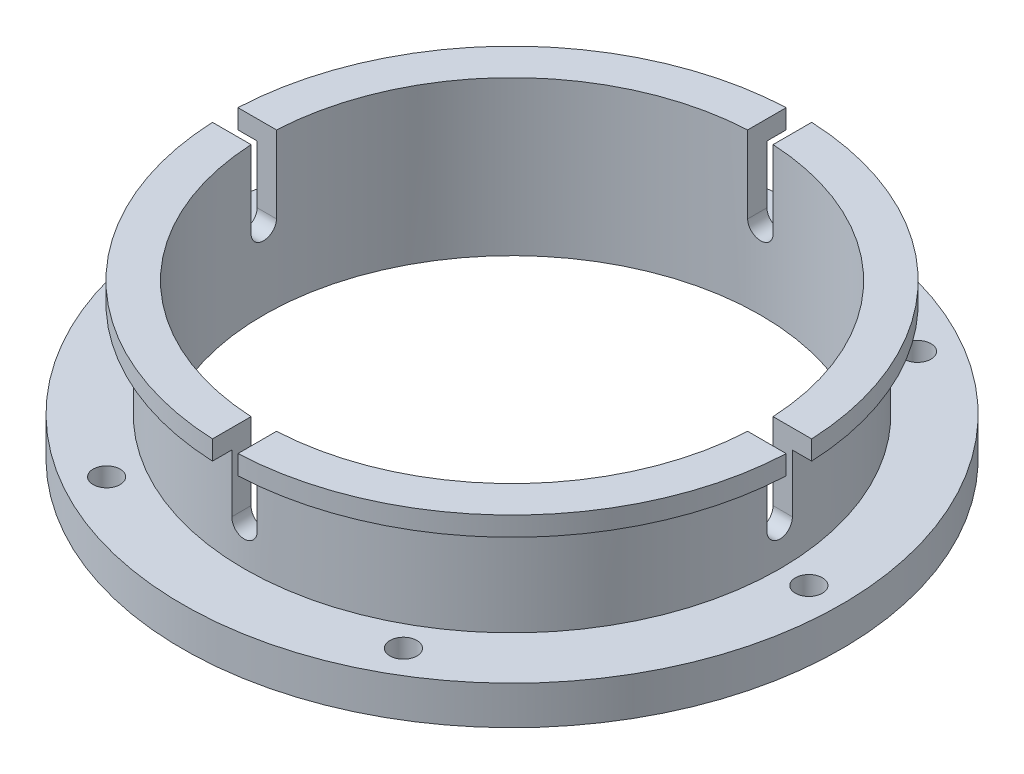
SolidWorks part; units mm, degrees
ref_plane "Front Plane" through (0, 0, 0) normal (0, 0, 1) x (1, 0, 0)
ref_plane "Top Plane" through (0, 0, 0) normal (0, 1, 0) x (1, 0, 0)
ref_plane "Right Plane" through (0, 0, 0) normal (1, 0, 0) x (0, 0, -1)
sketch "Sketch1" plane through (0, 0, 0) normal (0, 1, 0) x (1, 0, 0)
  circle A0 centre (0, 0) radius 32.45
  dimension "D1" = 64.9
sketch "Sketch2" plane through (0, 0, 0) normal (0, 0, 1) x (1, 0, 0)
  line L0 (-32.25, 20) -> (-32.25, 0)
  line L1 (32.45, 0) -> (-32.45, 0) construction
  line L2 (-32.25, 20) -> (-37.25, 20)
  line L3 (-37.25, 20) -> (-37.25, 17.5)
  line L4 (-37.25, 17.5) -> (-34.75, 17.5)
  line L5 (-34.75, 17.5) -> (-34.75, 5)
  line L6 (-34.75, 5) -> (-42.75, 5)
  line L7 (-42.75, 5) -> (-42.75, 0)
  line L8 (-42.75, 0) -> (-32.25, 0)
  line L9 (0, 0) -> (0, 50000) construction
  dimension "D1" = 10.5
  dimension "D2" = 2.5
  dimension "D3" = 5
  dimension "D4" = 2.5
  dimension "D5" = 20
  dimension "D6" = 5
  dimension "D7" = 2.5
  dimension "D8" = 32.25
revolve "Revolve1" add sketch "Sketch2" angle 360 about L9
sketch "Sketch3" plane through (0, 0, 0) normal (1, 0, 0) x (0, 0, -1)
  line L0 (37.25, 20) -> (-37.25, 20) construction
  line L1 (-1.65, 30) -> (1.65, 30)
  line L2 (-1.65, 30) -> (-1.65, 10)
  line L4 (1.65, 30) -> (1.65, 10)
  line L5 (-1.65, 30) -> (1.65, 10) construction
  line L6 (-1.65, 10) -> (1.65, 30) construction
  arc A0 (-1.65, 10) -> (1.65, 10) centre (0, 10) ccw
  point P0 (0, 20)
  dimension "D2" = 1.65
  dimension "D1" = 3.3
  dimension "D3" = 10
extrude "Cut-Extrude1" cut sketch "Sketch3" against normal through all both and the other way through all
pattern_circular "CirPattern1" count 4 over 360 about axis through (0, 0, 0) along (0, -1, 0) of "Cut-Extrude1"
sketch "Sketch4" plane through (0, 5, 0) normal (0, 1, 0) x (1, 0, 0)
  circle A0 centre (-38.5, 0) radius 1.75
  circle A1 centre (-38.5, 0) radius 3.5 construction
  dimension "D1" = 3.5
  dimension "D3" = 7
  dimension "D2" = 38.5
extrude "Cut-Extrude2" cut sketch "Sketch4" against normal blind 10
pattern_circular "CirPattern2" count 6 over 360 about axis through (0, 0, 0) along (0, 1, 0) of "Cut-Extrude2"
equation "\"D8@Sketch2\"=64.5/2"
